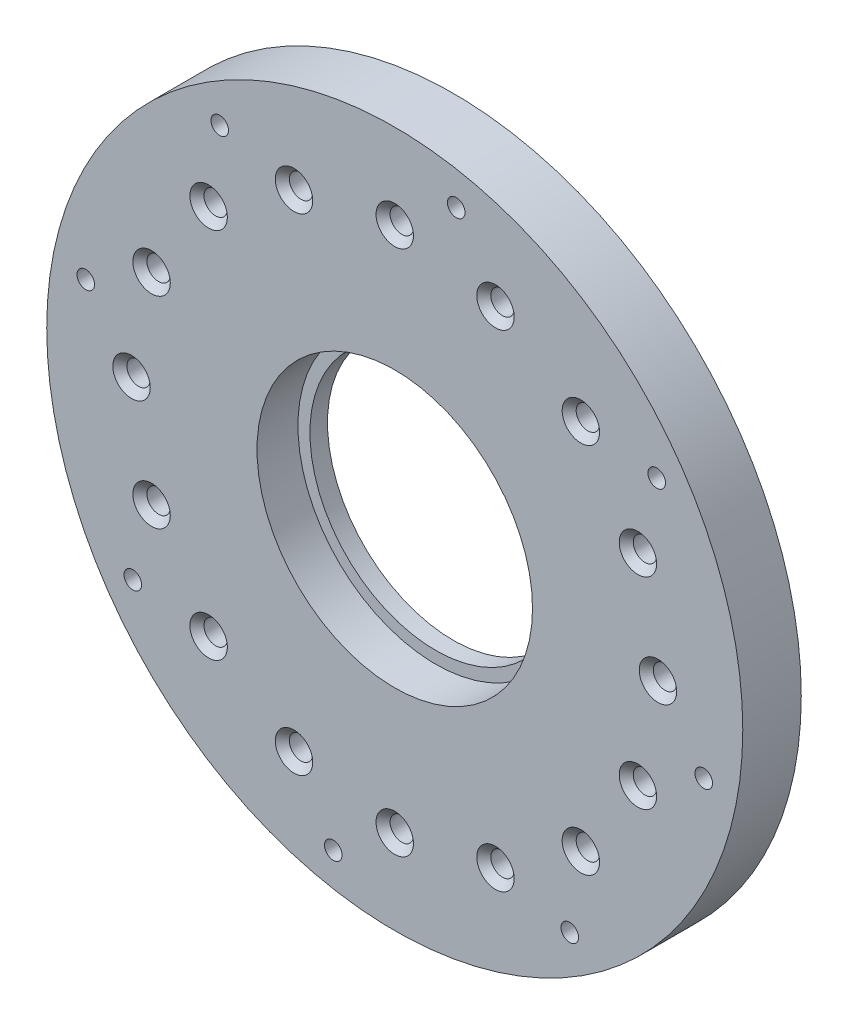
SolidWorks part; units mm, degrees
ref_plane "Front Plane" through (0, 0, 0) normal (0, 0, 1) x (1, 0, 0)
ref_plane "Top Plane" through (0, 0, 0) normal (0, 1, 0) x (1, 0, 0)
ref_plane "Right Plane" through (0, 0, 0) normal (1, 0, 0) x (0, 0, -1)
sketch "Sketch3" plane through (0, 0, 0) normal (0, 0, 1) x (1, 0, 0)
  circle A0 centre (0, 0) radius 59.5
  dimension "D1" = 119
extrude "Boss-Extrude1" add sketch "Sketch3" along normal blind 10
sketch "Sketch4" plane through (0, 0, 10) normal (0, 0, 1) x (1, 0, 0)
  line L0 (0, 0) -> (80.3371, 0) construction
  line L1 (0, 0) -> (65.7826, 43.9545) construction
  circle A0 centre (0, 0) radius 53.86 construction
  circle A1 centre (44.783, 29.923) radius 1.5
  circle A2 centre (52.8251, -10.5076) radius 1.5
  circle A3 centre (29.923, -44.783) radius 1.5
  circle A4 centre (-10.5076, -52.8251) radius 1.5
  circle A5 centre (-44.783, -29.923) radius 1.5
  circle A6 centre (-52.8251, 10.5076) radius 1.5
  circle A7 centre (-29.923, 44.783) radius 1.5
  circle A8 centre (10.5076, 52.8251) radius 1.5
  point P5 (44.783, 29.923)
  point P25 (0, 0)
  dimension "D1" = 107.72
  dimension "D2" = 3
  dimension "D3" = 8
extrude "Cut-Extrude1" cut sketch "Sketch4" against normal through all
sketch "Sketch5" plane through (0, 0, 10) normal (0, 0, 1) x (1, 0, 0)
  line L0 (0, 0) -> (91.3259, 0) construction
  circle A0 centre (0, 0) radius 45 construction
  circle A1 centre (45, 0) radius 2
  circle A2 centre (41.5746, -17.2208) radius 2
  circle A3 centre (31.8198, -31.8198) radius 2
  circle A4 centre (17.2208, -41.5746) radius 2
  circle A5 centre (0, -45) radius 2
  circle A6 centre (-17.2208, -41.5746) radius 2
  circle A7 centre (-31.8198, -31.8198) radius 2
  circle A8 centre (-41.5746, -17.2208) radius 2
  circle A9 centre (-45, 0) radius 2
  circle A10 centre (-41.5746, 17.2208) radius 2
  circle A11 centre (-31.8198, 31.8198) radius 2
  circle A12 centre (-17.2208, 41.5746) radius 2
  circle A13 centre (0, 45) radius 2
  circle A14 centre (17.2208, 41.5746) radius 2
  circle A15 centre (31.8198, 31.8198) radius 2
  circle A16 centre (41.5746, 17.2208) radius 2
  point P38 (0, 0)
  dimension "D1" = 90
  dimension "D2" = 4
  dimension "D3" = 16
extrude "Cut-Extrude2" cut sketch "Sketch5" against normal blind 5
sketch "Sketch6" plane through (0, 0, 0) normal (0, 0, -1) x (-1, 0, 0)
  line L0 (0, 0) -> (52.8251, 10.5076) construction
  circle A0 centre (52.8251, 10.5076) radius 2.9
  circle A1 centre (44.783, -29.923) radius 2.9
  circle A2 centre (10.5076, -52.8251) radius 2.9
  circle A3 centre (-29.923, -44.783) radius 2.9
  circle A4 centre (-52.8251, -10.5076) radius 2.9
  circle A5 centre (-44.783, 29.923) radius 2.9
  circle A6 centre (-10.5076, 52.8251) radius 2.9
  circle A7 centre (29.923, 44.783) radius 2.9
  point P22 (0, 0)
  dimension "D1" = 5.8
  dimension "D2" = 8
extrude "Cut-Extrude3" cut sketch "Sketch6" against normal blind 3
sketch "Sketch7" plane through (0, 0, 10) normal (0, 0, 1) x (1, 0, 0)
  circle A0 centre (0, 0) radius 23.55
  dimension "D1" = 47.1
extrude "Cut-Extrude4" cut sketch "Sketch7" against normal blind 7
sketch "Sketch8" plane through (0, 0, 10) normal (0, 0, 1) x (1, 0, 0)
  circle A0 centre (0, 0) radius 21.5
  dimension "D1" = 43
extrude "Cut-Extrude5" cut sketch "Sketch8" against normal through all
chamfer "Chamfer1" distance 1.2 angle 45 16 edges at (-39.5746, 17.2208, 10) (-43, 0, 10) (-39.5746, -17.2208, 10) (-29.8198, -31.8198, 10) (-15.2208, -41.5746, 10) (2, -45, 10) (2, 45, 10) (19.2208, -41.5746, 10) (33.8198, -31.8198, 10) (43.5746, -17.2208, 10) (47, 0, 10) (43.5746, 17.2208, 10) (33.8198, 31.8198, 10) (19.2208, 41.5746, 10) (-15.2208, 41.5746, 10) (-29.8198, 31.8198, 10)
